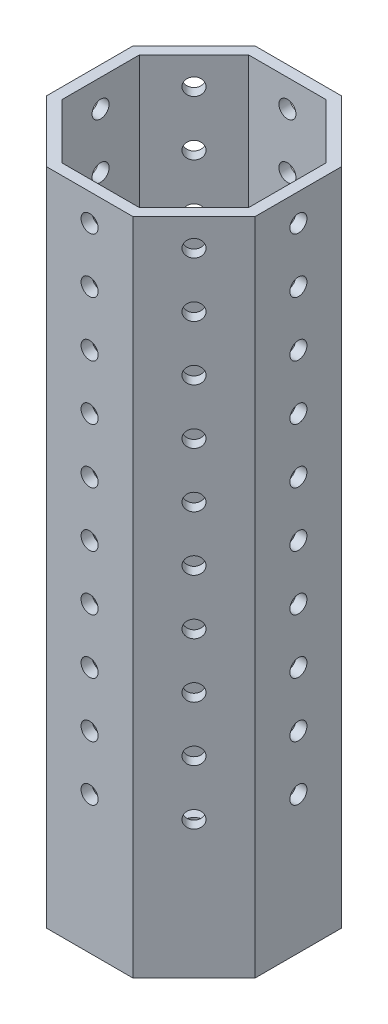
SolidWorks part; units mm, degrees
ref_plane "Alzado" through (0, 0, 0) normal (0, 0, 1) x (1, 0, 0)
ref_plane "Planta" through (0, 0, 0) normal (0, 1, 0) x (1, 0, 0)
ref_plane "Vista lateral" through (0, 0, 0) normal (1, 0, 0) x (0, 0, -1)
sketch "Croquis1" plane through (0, 0, 0) normal (0, 1, 0) x (1, 0, 0)
  line L0 (0, 0) -> (0, 30.3027) construction
  line L1 (19, -7.8701) -> (19, 7.8701)
  line L2 (19, 7.8701) -> (7.8701, 19)
  line L3 (7.8701, 19) -> (-7.8701, 19)
  line L4 (-7.8701, 19) -> (-19, 7.8701)
  line L5 (-19, 7.8701) -> (-19, -7.8701)
  line L6 (-19, -7.8701) -> (-7.8701, -19)
  line L7 (-7.8701, -19) -> (7.8701, -19)
  line L8 (7.8701, -19) -> (19, -7.8701)
  circle A0 centre (0, 0) radius 19 construction
  circle A1 centre (0, 11) radius 1.55
  circle A2 centre (0, 0) radius 4
  circle A3 centre (7.7782, 7.7782) radius 1.55
  circle A4 centre (11, 0) radius 1.55
  circle A5 centre (7.7782, -7.7782) radius 1.55
  circle A6 centre (0, -11) radius 1.55
  circle A7 centre (-7.7782, -7.7782) radius 1.55
  circle A8 centre (-11, 0) radius 1.55
  circle A9 centre (-7.7782, 7.7782) radius 1.55
  point P32 (0, 0)
  dimension "D1" = 38
  dimension "D2" = 3.1
  dimension "D3" = 11
  dimension "D4" = 8
  dimension "D5" = 8
extrude "Saliente-Extruir1" add sketch "Croquis1" along normal blind 120
sketch "Croquis2" plane through (0, 120, 0) normal (0, 1, 0) x (1, 0, 0)
  line L0 (7.8701, 19) -> (-7.8701, 19) construction
  line L1 (7.0416, 17) -> (-7.0416, 17)
  line L2 (-7.0416, 17) -> (-17, 7.0416)
  line L3 (-17, 7.0416) -> (-17, -7.0416)
  line L4 (-17, -7.0416) -> (-7.0416, -17)
  line L5 (-7.0416, -17) -> (7.0416, -17)
  line L6 (7.0416, -17) -> (17, -7.0416)
  line L7 (17, -7.0416) -> (17, 7.0416)
  line L8 (17, 7.0416) -> (7.0416, 17)
  line L9 (-19, 7.8701) -> (-19, -7.8701) construction
  circle A0 centre (0, 0) radius 17 construction
  dimension "D1" = 2
extrude "Cortar-Extruir1" cut sketch "Croquis2" against normal offset from surface (117 mm away) 3 up to face at (0, 0, 0)
sketch "Croquis3" plane through (0, 0, -19) normal (0, 0, -1) x (-1, 0, 0)
  line L0 (-7.8701, 120) -> (7.8701, 120) construction
  circle A0 centre (0, 115) radius 1.55
  circle A1 centre (0, 105) radius 1.55
  circle A2 centre (0, 95) radius 1.55
  circle A3 centre (0, 85) radius 1.55
  circle A4 centre (0, 75) radius 1.55
  circle A5 centre (0, 65) radius 1.55
  circle A6 centre (0, 55) radius 1.55
  circle A7 centre (0, 45) radius 1.55
  circle A8 centre (0, 35) radius 1.55
  circle A9 centre (0, 25) radius 1.55
  dimension "D1" = 3.1
  dimension "D2" = 5
  dimension "D3" = 10
extrude "Cortar-Extruir2" cut sketch "Croquis3" against normal up to next
pattern_circular "MatrizC1" count 8 over 360 about axis through (0, 3, 0) along (0, 1, 0) of "Cortar-Extruir2"
